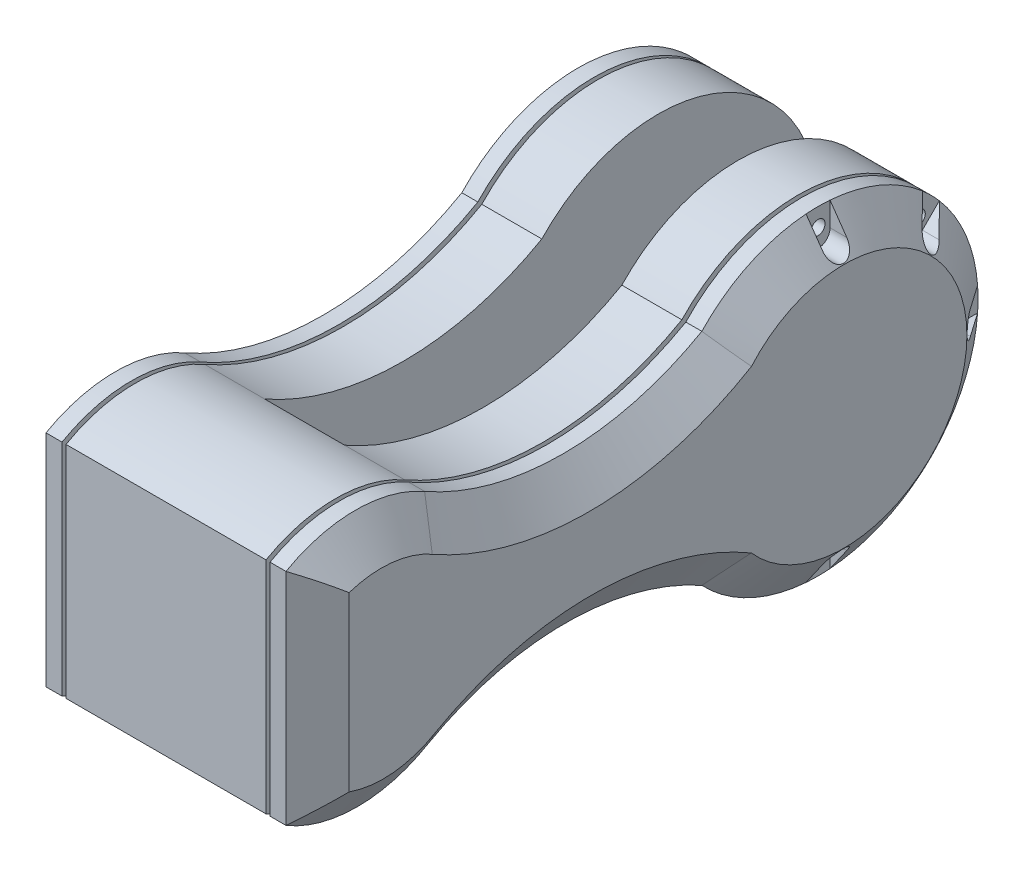
SolidWorks part; units mm, degrees
material "1023 Carbon Steel Sheet (SS)"
ref_plane "Front Plane" through (0, 0, 0) normal (0, 0, 1) x (1, 0, 0)
ref_plane "Top Plane" through (0, 0, 0) normal (0, 1, 0) x (1, 0, 0)
ref_plane "Right Plane" through (0, 0, 0) normal (1, 0, 0) x (0, 0, -1)
sketch "Sketch1" plane through (0, 0, 0) normal (0, 0, 1) x (1, 0, 0)
  line L0 (0, 0) -> (27.5, 0) construction
  line L1 (27.5, -20) -> (27.5, 20) construction
  line L2 (0, 0) -> (27.5, 0)
  line L3 (27.5, 0) -> (27.5, 7.4104)
  line L4 (27.5, 7.4104) -> (0, 7.4104)
  line L5 (0, 7.4104) -> (0, 0)
  point P7 (27.5, 0)
  dimension "D1" = 27.5
  dimension "D2" = 27.5
  dimension "D3" = 20
extrude "Boss-Extrude1" add sketch "Sketch1" along normal blind 1
ref_plane "Plane1" through (27.5, 0, 0) normal (1, 0, 0) x (0, 0, -1)
sketch "Sketch2" plane through (27.5, 0, 0) normal (1, 0, 0) x (0, 0, -1)
  line L1 (-1, 27.5) -> (-1, -27.5)
  line L2 (-1, 0) -> (22, 0) construction
  arc A0 (-1, 27.5) -> (33.6509, 27.5) centre (16.3254, -2.911) cw
  arc A1 (33.6509, 27.5) -> (102.9526, 27.5) centre (68.3017, 88.322) ccw
  arc A2 (34.6509, -27.5) -> (102.9526, -27.5) centre (68.8017, -88.6042) cw
  arc A3 (-1, -27.5) -> (34.6509, -27.5) centre (16.8254, 2.6207) ccw
  arc A4 (102.9526, -27.5) -> (102.9526, 27.5) centre (132, 0) ccw
  dimension "D2" = 70
  dimension "D3" = 80
  dimension "D5" = 35
  dimension "D1" = 23
  dimension "D4" = 110
extrude "Boss-Extrude3" add sketch "Sketch2" along normal blind 15 separate body
sketch "Sketch3" plane through (42.5, 0, 0) normal (1, 0, 0) x (0, 0, -1)
  line L7 (1.5, 26.0106) -> (1.5, -26.0391)
  line L8 (1.5, 26.0106) -> (1.5, -26.0391)
  arc A24 (1.5, -26.0391) -> (33.4035, -25.3332) centre (16.8254, 2.6207) ccw
  arc A25 (104.5134, -25.5096) -> (33.4035, -25.3332) centre (68.8017, -88.6042) ccw
  arc A26 (104.5134, -25.5096) -> (104.5204, 25.5171) centre (132, 0) ccw
  arc A27 (32.4133, 25.3278) -> (104.5204, 25.5171) centre (68.3017, 88.322) ccw
  arc A28 (32.4133, 25.3278) -> (1.5, 26.0106) centre (16.3254, -2.911) ccw
  arc A29 (1.5, -26.0391) -> (33.4035, -25.3332) centre (16.8254, 2.6207) ccw
  arc A30 (104.5134, -25.5096) -> (33.4035, -25.3332) centre (68.8017, -88.6042) ccw
  arc A31 (104.5134, -25.5096) -> (104.5204, 25.5171) centre (132, 0) ccw
  arc A32 (32.4133, 25.3278) -> (104.5204, 25.5171) centre (68.3017, 88.322) ccw
  arc A33 (32.4133, 25.3278) -> (1.5, 26.0106) centre (16.3254, -2.911) ccw
  dimension "D1" = 2.5
extrude "Boss-Extrude4" add sketch "Sketch3" along normal blind 1
sketch "Sketch4" plane through (43.5, 0, 0) normal (1, 0, 0) x (0, 0, -1)
  line L2 (-1, 27.5) -> (-1, -27.5)
  line L3 (-1, 27.5) -> (-1, -27.5)
  arc A10 (-1, -27.5) -> (34.6509, -27.5) centre (16.8254, 2.6207) ccw
  arc A11 (102.9526, -27.5) -> (34.6509, -27.5) centre (68.8017, -88.6042) ccw
  arc A12 (102.9526, -27.5) -> (102.9526, 27.5) centre (132, 0) ccw
  arc A13 (33.6509, 27.5) -> (102.9526, 27.5) centre (68.3017, 88.322) ccw
  arc A14 (33.6509, 27.5) -> (-1, 27.5) centre (16.3254, -2.911) ccw
  arc A15 (-1, -27.5) -> (34.6509, -27.5) centre (16.8254, 2.6207) ccw
  arc A16 (102.9526, -27.5) -> (34.6509, -27.5) centre (68.8017, -88.6042) ccw
  arc A17 (102.9526, -27.5) -> (102.9526, 27.5) centre (132, 0) ccw
  arc A18 (33.6509, 27.5) -> (102.9526, 27.5) centre (68.3017, 88.322) ccw
  arc A19 (33.6509, 27.5) -> (-1, 27.5) centre (16.3254, -2.911) ccw
  dimension "D1" = 2.5
extrude "Boss-Extrude5" add sketch "Sketch4" along normal blind 4
sketch "Sketch5" plane through (47.5, 0, 0) normal (1, 0, 0) x (0, 0, -1)
  line L0 (-1, 27.5) -> (-1, -27.5) construction
  line L1 (-1, 27.5) -> (-1, -27.5)
  arc A0 (-1, -27.5) -> (34.6509, -27.5) centre (16.8254, 2.6207) ccw construction
  arc A1 (102.9526, -27.5) -> (34.6509, -27.5) centre (68.8017, -88.6042) ccw construction
  arc A2 (102.9526, -27.5) -> (102.9526, 27.5) centre (132, 0) ccw construction
  arc A3 (33.6509, 27.5) -> (102.9526, 27.5) centre (68.3017, 88.322) ccw construction
  arc A4 (33.6509, 27.5) -> (-1, 27.5) centre (16.3254, -2.911) ccw construction
  arc A5 (-1, -27.5) -> (34.6509, -27.5) centre (16.8254, 2.6207) ccw
  arc A6 (102.9526, -27.5) -> (34.6509, -27.5) centre (68.8017, -88.6042) ccw
  arc A7 (102.9526, -27.5) -> (102.9526, 27.5) centre (132, 0) ccw
  arc A8 (33.6509, 27.5) -> (102.9526, 27.5) centre (68.3017, 88.322) ccw
  arc A9 (33.6509, 27.5) -> (-1, 27.5) centre (16.3254, -2.911) ccw
extrude "Boss-Extrude6" add sketch "Sketch5" along normal blind 6.5 draft 55
sketch "Sketch6" plane through (54, 0, 0) normal (1, 0, 0) x (0, 0, -1)
  line L0 (0, 0) -> (172, 0) construction
  line L1 (171.8873, 3) -> (165.8873, 3)
  line L2 (171.8873, -3) -> (165.8873, -3)
  arc A0 (102.9526, -27.5) -> (102.9526, 27.5) centre (132, 0) ccw construction
  arc A1 (165.8873, 3) -> (165.8873, -3) centre (165.8873, 0) ccw
  arc A2 (171.8873, 3) -> (171.8873, -3) centre (167.8873, 0) cw
  dimension "D3" = 3
  dimension "D4" = 5
  dimension "D1" = 3
  dimension "D2" = 6
extrude "Cut-Extrude1" cut sketch "Sketch6" against normal blind 6.5
sketch "Sketch8" plane through (47.5, 0, 0) normal (1, 0, 0) x (0, 0, -1)
  line L0 (172, 0) -> (162.8873, 0) construction
  arc A0 (171.8873, -3) -> (171.8873, 3) centre (132, 0) ccw construction
  arc A1 (165.8873, 3) -> (165.8873, -3) centre (165.8873, 0) ccw construction
  circle A2 centre (167.4437, 0) radius 1.75
  dimension "D1" = 3.5
extrude "Cut-Extrude2" cut sketch "Sketch8" against normal blind 5
pattern_circular "CirPattern1" count 3 every 45 about axis through (0, 0, -132) along (1, 0, 0) of "Cut-Extrude1", "Cut-Extrude2"
sketch "Sketch9" plane through (27.5, 0, 0) normal (-1, 0, 0) x (0, 0, 1)
  line L0 (-33.6509, 27.5) -> (-34.6509, -27.5)
  line L1 (1, -27.5) -> (1, 27.5)
  line L2 (1, -27.5) -> (1, 27.5)
  arc A5 (1, 27.5) -> (-33.6509, 27.5) centre (-16.3254, -2.911) ccw
  arc A6 (-102.9526, 27.5) -> (-33.6509, 27.5) centre (-68.3017, 88.322) ccw
  arc A7 (-102.9526, 27.5) -> (-102.9526, -27.5) centre (-132, 0) ccw
  arc A8 (-34.6509, -27.5) -> (-102.9526, -27.5) centre (-68.8017, -88.6042) ccw
  arc A9 (-34.6509, -27.5) -> (1, -27.5) centre (-16.8254, 2.6207) ccw
  arc A10 (1, 27.5) -> (-33.6509, 27.5) centre (-16.3254, -2.911) ccw
  arc A14 (-34.6509, -27.5) -> (1, -27.5) centre (-16.8254, 2.6207) ccw
  dimension "D1" = 0
extrude "Boss-Extrude7" add sketch "Sketch9" along normal blind 20
ref_plane "Plane2" through (17.5, 0, 0) normal (-1, 0, 0) x (0, 0, 1)
mirror "Mirror2" about plane through (17.5, 0, 0) normal (-1, 0, 0) of bodies 110
